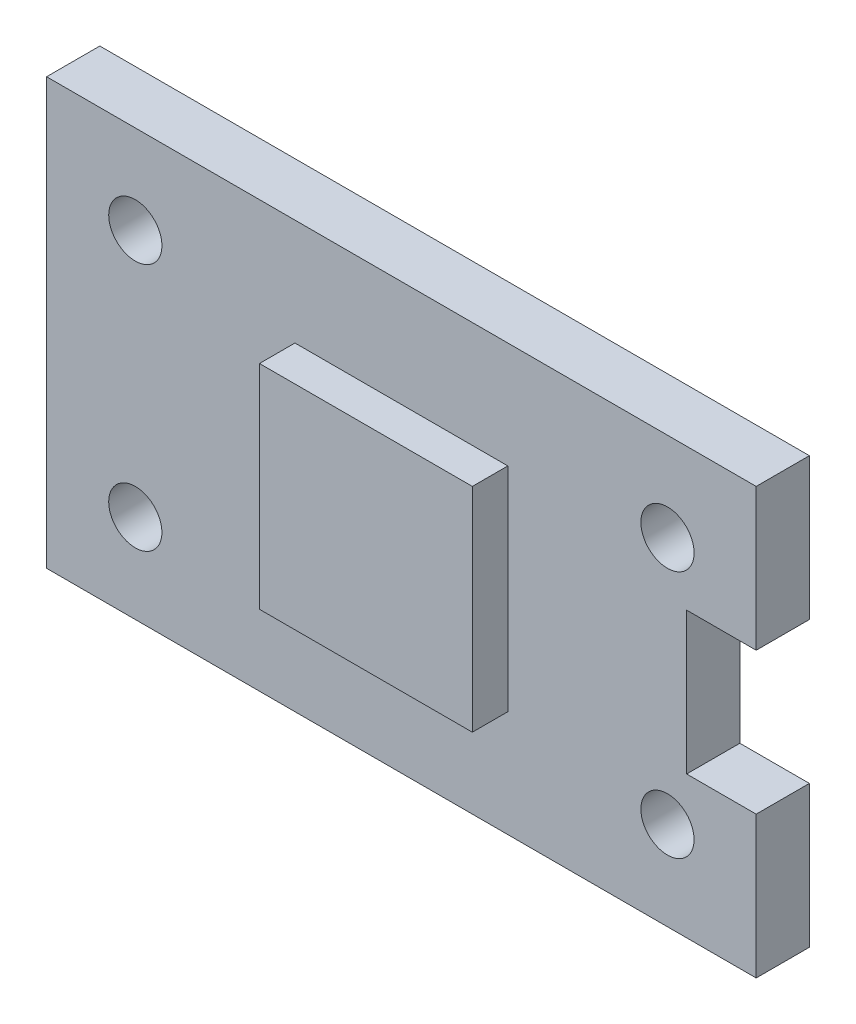
SolidWorks part; units mm, degrees
ref_plane "Front Plane" through (0, 0, 0) normal (0, 0, 1) x (1, 0, 0)
ref_plane "Top Plane" through (0, 0, 0) normal (0, 1, 0) x (1, 0, 0)
ref_plane "Right Plane" through (0, 0, 0) normal (1, 0, 0) x (0, 0, -1)
sketch "Sketch1" plane through (0, 0, 0) normal (0, 0, 1) x (1, 0, 0)
  line L1 (0, 0) -> (127, 0)
  line L2 (0, 0) -> (0, 76.2)
  line L3 (0, 76.2) -> (127, 76.2)
  line L4 (127, 0) -> (127, 76.2)
extrude "base_plate" add sketch "Sketch1" along normal blind 9.525
ref_plane "plane_top" through (0, 0, 9.525) normal (0, 0, 1) x (1, 0, 0)
sketch "Sketch2" plane through (0, 0, 9.525) normal (0, 0, 1) x (1, 0, 0)
  line L1 (44.45, 19.05) -> (82.55, 19.05)
  line L2 (44.45, 19.05) -> (44.45, 57.15)
  line L3 (44.45, 57.15) -> (82.55, 57.15)
  line L4 (82.55, 19.05) -> (82.55, 57.15)
extrude "raised_boss" add sketch "Sketch2" along normal blind 6.35
sketch "Sketch3" plane through (0, 0, 0) normal (0, 0, 1) x (1, 0, 0)
  line L1 (114.554, 25.4) -> (127.254, 25.4)
  line L2 (114.554, 25.4) -> (114.554, 50.8)
  line L3 (114.554, 50.8) -> (127.254, 50.8)
  line L4 (127.254, 25.4) -> (127.254, 50.8)
extrude "edge_notch" cut sketch "Sketch3" along normal through all
sketch "Sketch4" plane through (0, 0, 0) normal (0, 0, 1) x (1, 0, 0)
  circle A0 centre (15.875, 15.875) radius 4.7625
extrude "hole_1" cut sketch "Sketch4" along normal through all
sketch "Sketch5" plane through (0, 0, 0) normal (0, 0, 1) x (1, 0, 0)
  circle A0 centre (111.125, 15.875) radius 4.7625
extrude "hole_2" cut sketch "Sketch5" along normal through all
sketch "Sketch6" plane through (0, 0, 0) normal (0, 0, 1) x (1, 0, 0)
  circle A0 centre (15.875, 60.325) radius 4.7625
extrude "hole_3" cut sketch "Sketch6" along normal through all
sketch "Sketch7" plane through (0, 0, 0) normal (0, 0, 1) x (1, 0, 0)
  circle A0 centre (111.125, 60.325) radius 4.7625
extrude "hole_4" cut sketch "Sketch7" along normal through all
sketch "Sketch8" plane through (0, 0, 0) normal (0, 0, 1) x (1, 0, 0)
  circle A0 centre (63.5, 38.1) radius 9.525
sketch "Sketch9" plane through (0, 0, 0) normal (0, 0, 1) x (1, 0, 0)
  circle A0 centre (25.4, 38.1) radius 3.175
